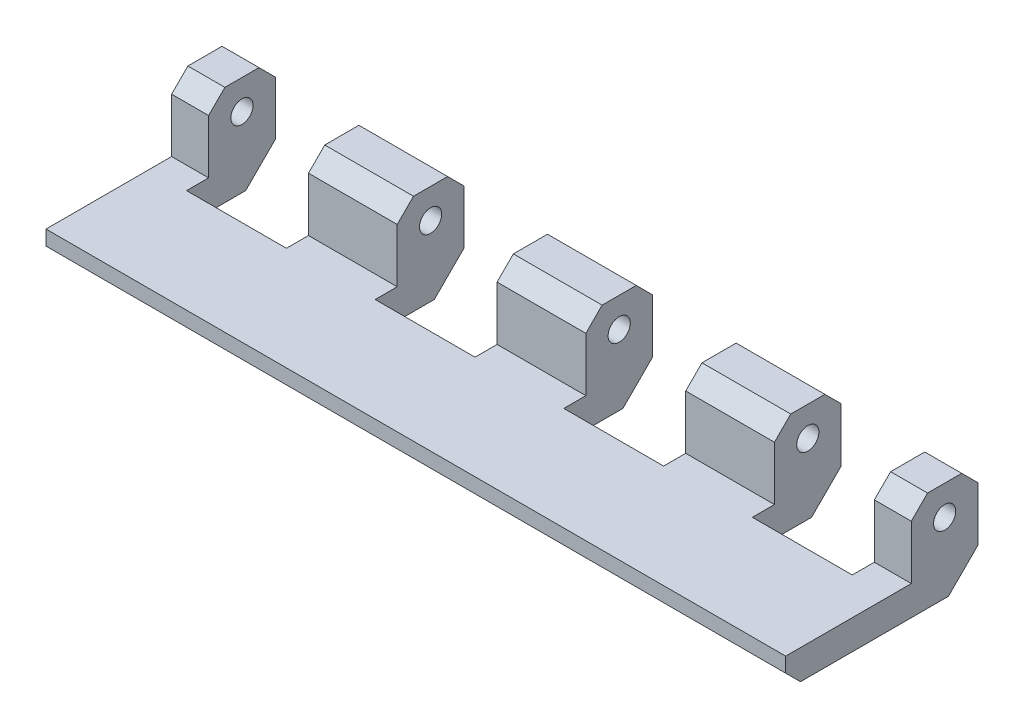
SolidWorks part; units mm, degrees
ref_plane "Спереди" through (0, 0, 0) normal (0, 0, 1) x (1, 0, 0)
ref_plane "Сверху" through (0, 0, 0) normal (0, 1, 0) x (1, 0, 0)
ref_plane "Справа" through (0, 0, 0) normal (1, 0, 0) x (0, 0, -1)
sketch "Эскиз1" plane through (0, 0, 0) normal (0, 1, 0) x (1, 0, 0)
  line L1 (-24, 0) -> (76, 0)
  line L2 (-24, 0) -> (-24, -26)
  line L3 (-24, -26) -> (76, -26)
  line L4 (76, 0) -> (76, -26)
extrude "Вытянуть1" add sketch "Эскиз1" along normal blind 13.5
sketch "Эскиз2" plane through (76, 0, 0) normal (1, 0, 0) x (0, 0, -1)
  line L0 (4.8026, 4) -> (-2.9217, 4) construction
  line L1 (-26, 13.5) -> (0, 13.5) construction
  line L3 (-28.123, 13.5) -> (-9.0163, 13.5)
  line L4 (-28.123, 13.5) -> (-28.123, 4)
  line L5 (-28.123, 4) -> (-9.0163, 4)
  line L6 (-9.0163, 13.5) -> (-9.0163, 4)
  line L7 (-26, 0) -> (0, 0) construction
  dimension "D1" = 4
extrude "Вырез-Вытянуть1" cut sketch "Эскиз2" against normal through all
chamfer "Фаска1" distance 2.2 angle 45 2 edges at (26, 13.5, 0) (26, 13.5, 9.0163)
chamfer "Фаска2" distance 4 angle 45 1 edges at (26, 0, 0)
sketch "Эскиз3" plane through (76, 0, 0) normal (1, 0, 0) x (0, 0, -1)
  line L0 (-4.5081, 12) -> (-4.5081, 13.7201) construction
  line L1 (-6.8163, 13.5) -> (-2.2, 13.5) construction
  circle A0 centre (-4.5081, 9.5) radius 1.5
  dimension "D1" = 4
extrude "Вырез-Вытянуть2" cut sketch "Эскиз3" against normal through all
sketch "Эскиз4" plane through (0, 13.5, 0) normal (0, 1, 0) x (1, 0, 0)
  line L3 (-19, -12) -> (-19, 0)
  line L4 (-5.5, -12) -> (-19, -12)
  line L5 (-5.5, 0) -> (-19, 0)
  line L6 (57.5, -12) -> (71, -12)
  line L7 (57.5, -12) -> (57.5, 0)
  line L8 (-5.5, -12) -> (-5.5, 0)
  line L9 (57.5, 0) -> (71, 0)
  line L10 (71, -12) -> (71, 0)
  line L17 (-24, -2.2) -> (-24, -6.8163) construction
  line L18 (-15, -12) -> (-35.2516, -12) construction
  line L19 (-15, 0) -> (-37.8277, 0) construction
  line L20 (6.5, 0) -> (20, 0)
  line L21 (6.5, 0) -> (6.5, -12)
  line L22 (76, -6.8163) -> (76, -2.2) construction
  line L23 (6.5, -12) -> (20, -12)
  line L24 (20, 0) -> (20, -12)
  line L27 (32, 0) -> (45.5, 0)
  line L28 (32, 0) -> (32, -12)
  line L29 (32, -12) -> (45.5, -12)
  line L30 (45.5, 0) -> (45.5, -12)
  dimension "D1" = 5
  dimension "D2" = 5
  dimension "D3" = 13.5
  dimension "D4" = 12
  dimension "D5" = 13.5
  dimension "D6" = 12
  dimension "D7" = 13.5
extrude "Вырез-Вытянуть3" cut sketch "Эскиз4" against normal through all
chamfer "Фаска3" distance 2 angle 45 1 edges at (26, 0, 26)
